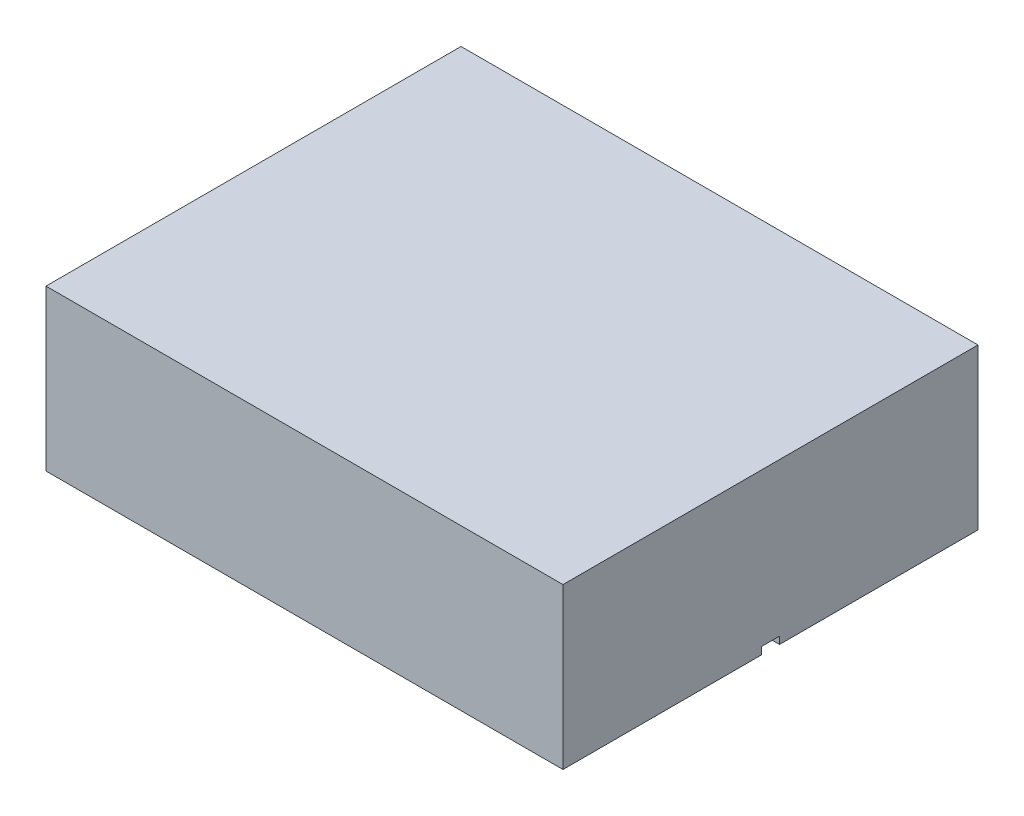
SolidWorks part; units mm, degrees
ref_plane "Front Plane" through (0, 0, 0) normal (0, 0, 1) x (1, 0, 0)
ref_plane "Top Plane" through (0, 0, 0) normal (0, 1, 0) x (1, 0, 0)
ref_plane "Right Plane" through (0, 0, 0) normal (1, 0, 0) x (0, 0, -1)
sketch "Sketch2" plane through (0, 0, 0) normal (0, 1, 0) x (1, 0, 0)
  line L1 (0, 0) -> (180.34, 0)
  line L2 (0, 0) -> (0, 144.78)
  line L3 (0, 144.78) -> (180.34, 144.78)
  line L4 (180.34, 0) -> (180.34, 144.78)
  dimension "D1" = 180.34
  dimension "D2" = 144.78
extrude "Boss-Extrude1" add sketch "Sketch2" along normal blind 55.88
sketch "Sketch4" plane through (0, 0, 0) normal (0, -1, 0) x (1, 0, 0)
  line L0 (0, -72.39) -> (180.34, -72.39) construction
  line L1 (0, -144.78) -> (0, 0) construction
  line L2 (180.34, 0) -> (180.34, -144.78) construction
  line L3 (0, -72.39) -> (2.54, -72.39) construction
  line L4 (0, -69.215) -> (2.54, -69.215)
  line L5 (0, -75.565) -> (2.54, -75.565)
  line L6 (90.17, 0) -> (90.17, -144.78) construction
  line L7 (0, 0) -> (180.34, 0) construction
  line L8 (180.34, -144.78) -> (0, -144.78) construction
  line L9 (180.34, -72.39) -> (177.8, -72.39) construction
  line L10 (180.34, -69.215) -> (177.8, -69.215)
  line L11 (180.34, -75.565) -> (177.8, -75.565)
  arc A0 (0, -69.215) -> (0, -75.565) centre (0, -72.39) ccw
  arc A1 (2.54, -75.565) -> (2.54, -69.215) centre (2.54, -72.39) ccw
  arc A2 (180.34, -69.215) -> (180.34, -75.565) centre (180.34, -72.39) cw
  arc A3 (177.8, -75.565) -> (177.8, -69.215) centre (177.8, -72.39) cw
  point P6 (1.27, -72.39)
  point P19 (179.07, -72.39)
  dimension "D1" = 2.54
  dimension "D2" = 6.35
extrude "Cut-Extrude2" cut sketch "Sketch4" against normal blind 2.54
sketch "Sketch3" plane through (0, 0, 0) normal (0, -1, 0) x (1, 0, 0)
  line L0 (0, -72.39) -> (180.34, -72.39) construction
  line L1 (0, -144.78) -> (0, -75.565) construction
  line L3 (90.17, 0) -> (90.17, -144.78) construction
  line L4 (0, 0) -> (180.34, 0) construction
  line L5 (180.34, -144.78) -> (0, -144.78) construction
  line L6 (0, -69.215) -> (0, -75.565) construction
  line L7 (180.34, 0) -> (180.34, -69.215) construction
  line L8 (0, -69.215) -> (0, 0) construction
  circle A0 centre (13.3825, -72.39) radius 2.54
  circle A1 centre (166.9575, -72.39) radius 2.54
  point P19 (0, -72.39)
  dimension "D1" = 5.08
  dimension "D2" = 13.3825
extrude "Cut-Extrude1" cut sketch "Sketch3" against normal blind 2.54
